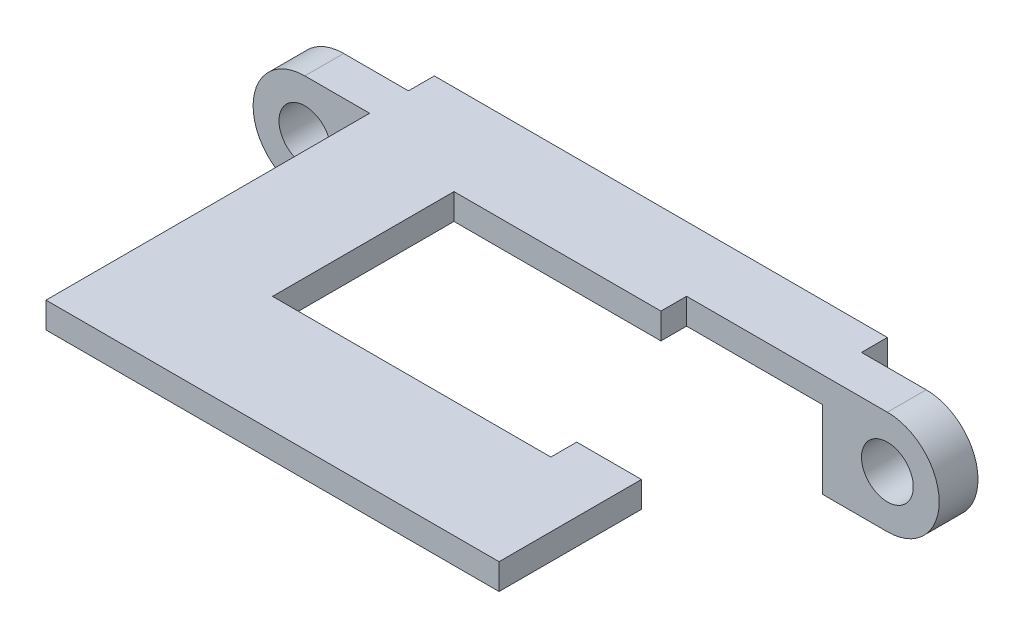
SolidWorks part; units mm, degrees
ref_plane "Alzado" through (0, 0, 0) normal (0, 0, 1) x (1, 0, 0)
ref_plane "Planta" through (0, 0, 0) normal (0, 1, 0) x (1, 0, 0)
ref_plane "Vista lateral" through (0, 0, 0) normal (1, 0, 0) x (0, 0, -1)
sketch "Croquis1" plane through (0, 0, 0) normal (0, 1, 0) x (1, 0, 0)
  line L0 (-17.5, 5) -> (-17.5, -5)
  line L1 (-17.5, 15) -> (-5, 15)
  line L2 (-17.5, 15) -> (-17.5, 5)
  line L3 (-17.5, -15) -> (17.5, -15)
  line L4 (17.5, 15) -> (17.5, 10)
  line L5 (-17.5, 15) -> (17.5, -15) construction
  line L6 (-17.5, -15) -> (17.5, 15) construction
  line L8 (-17.5, -5) -> (-17.5, -15)
  line L10 (-5, 15) -> (5, 15)
  line L14 (5, 15) -> (17.5, 15)
  line L15 (17.5, 15) -> (17.5, 10) construction
  line L16 (17.5, 10) -> (6.9869, 10)
  line L17 (-9, 8.0197) -> (-9, -6)
  line L18 (-9, -6) -> (12.5, -6)
  line L19 (17.5, -6) -> (17.5, -15)
  line L21 (17.5, -6) -> (17.5, -4)
  line L22 (17.5, -4) -> (12.5, -4)
  line L23 (12.5, -4) -> (12.5, -6)
  line L24 (-9, 10) -> (6.9869, 10) construction
  line L25 (6.9869, 10) -> (6.9869, 8.0197)
  line L26 (6.9869, 8.0197) -> (-9, 8.0197)
  point P0 (0, 0)
  dimension "D7" = 5
  dimension "D1" = 35
  dimension "D2" = 30
  dimension "D8" = 26.5
  dimension "D9" = 16
  dimension "D10" = 2
  dimension "D11" = 5
extrude "Saliente-Extruir3" add sketch "Croquis1" along normal blind 2
sketch "Croquis3" plane through (0, 0, -15) normal (0, 0, -1) x (-1, 0, 0)
  line L0 (-17.5, 2) -> (-17.5, -6)
  line L1 (-17.5, 2) -> (-22.5, 2)
  line L2 (-17.5, -6) -> (-22.5, -6)
  line L4 (17.5, 2) -> (17.5, -6)
  line L5 (17.5, 2) -> (22.5, 2)
  line L6 (17.5, -6) -> (22.5, -6)
  arc A0 (-22.5, 2) -> (-22.5, -6) centre (-22.5, -2) ccw
  arc A1 (22.5, -6) -> (22.5, 2) centre (22.5, -2) ccw
  circle A2 centre (-22.5, -2) radius 2
  circle A3 centre (22.5, -2) radius 2
  dimension "D3" = 4
  dimension "D1" = 5
  dimension "D2" = 8
ref_plane "Plano1" through (0, 0, -13) normal (0, 0, -1) x (-1, 0, 0)
extrude "Saliente-Extruir4" add sketch "Croquis3" against normal blind 3 from surface at -2 starting at plane "Plano1"
